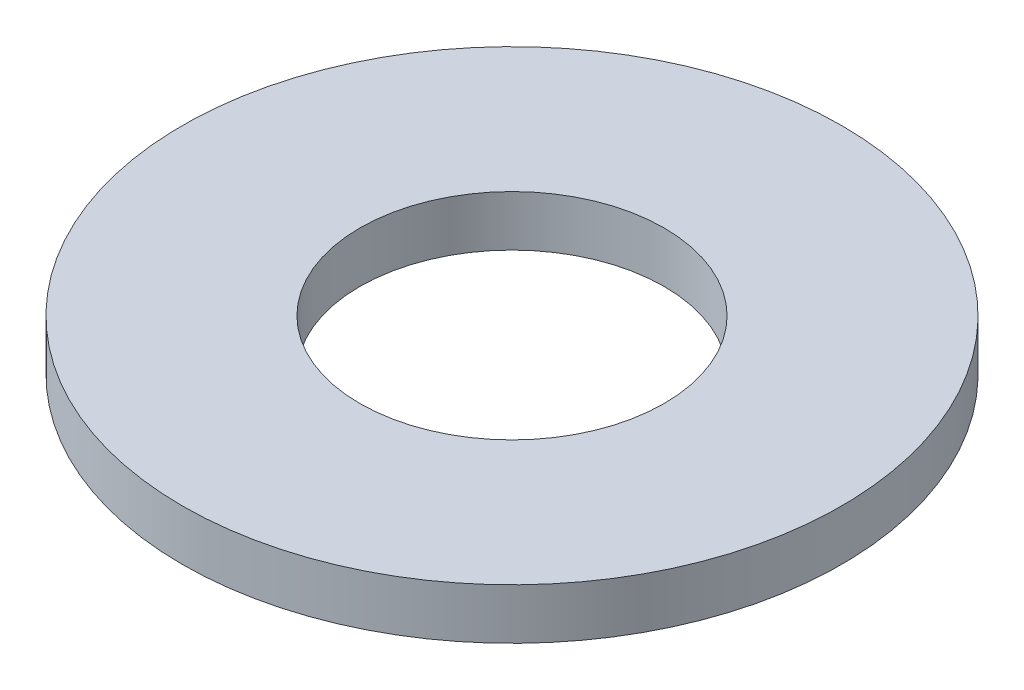
SolidWorks part; units mm, degrees
ref_plane "Front Plane" through (0, 0, 0) normal (0, 0, 1) x (1, 0, 0)
ref_plane "Top Plane" through (0, 0, 0) normal (0, 1, 0) x (1, 0, 0)
ref_plane "Right Plane" through (0, 0, 0) normal (1, 0, 0) x (0, 0, -1)
sketch "Sketch1" plane through (0, 0, 0) normal (0, 1, 0) x (1, 0, 0)
  circle A0 centre (0, 0) radius 13
  circle A1 centre (0, 0) radius 6
  dimension "D1" = 26
  dimension "D2" = 12
extrude "Boss-Extrude1" add sketch "Sketch1" along normal blind 2
